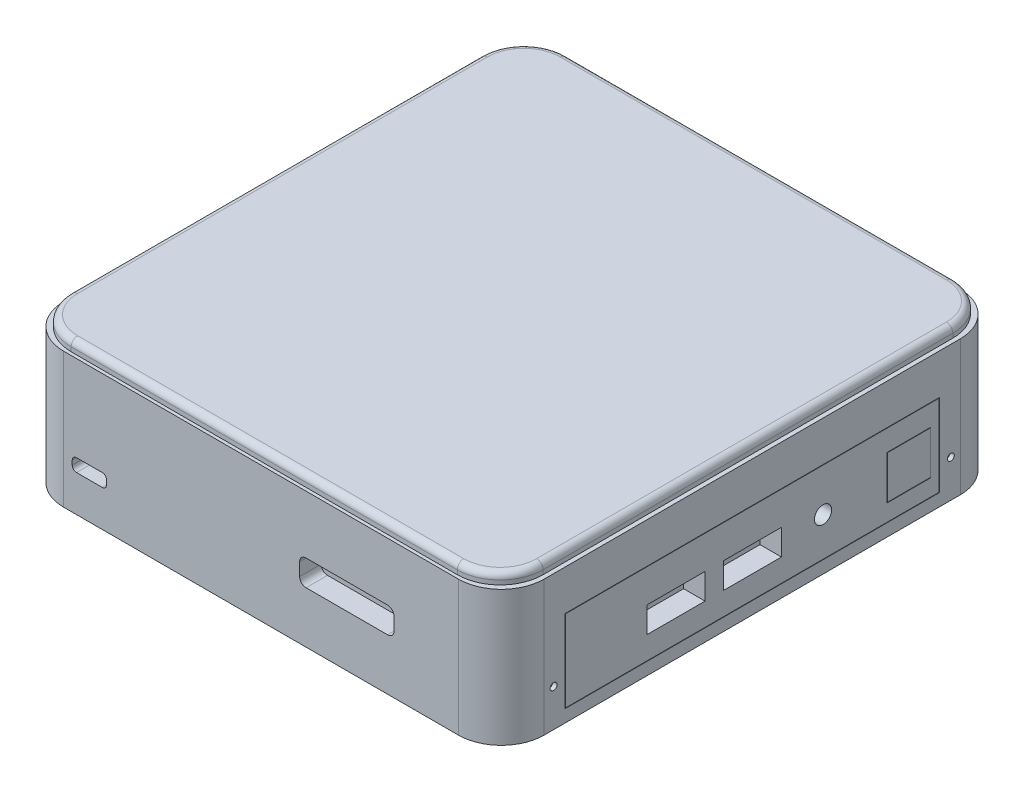
SolidWorks part; units mm, degrees
ref_plane "前视基准面" through (0, 0, 0) normal (0, 0, 1) x (1, 0, 0)
ref_plane "上视基准面" through (0, 0, 0) normal (0, 1, 0) x (1, 0, 0)
ref_plane "右视基准面" through (0, 0, 0) normal (1, 0, 0) x (0, 0, -1)
sketch "草图1" plane through (0, 0, 0) normal (0, 1, 0) x (1, 0, 0)
  line L1 (-56, 58.5) -> (56, 58.5)
  line L2 (-56, 58.5) -> (-56, -58.5)
  line L3 (-56, -58.5) -> (56, -58.5)
  line L4 (56, 58.5) -> (56, -58.5)
  line L5 (0, -58.5) -> (0, 58.5) construction
  line L6 (-56, 0) -> (56, 0) construction
  point P0 (0, 0)
  dimension "D1" = 117
  dimension "D2" = 112
extrude "凸台-拉伸1" add sketch "草图1" along normal blind 34
fillet "圆角1" radius 10 4 edges at (-56, 17, -58.5) (56, 17, -58.5) (56, 17, 58.5) (-56, 17, 58.5)
sketch "草图3" plane through (0, 0, 0) normal (0, 1, 0) x (1, 0, 0)
  line L1 (-44, 56.5) -> (44, 56.5)
  line L2 (-54, 46.5) -> (-54, -46.5)
  line L3 (-44, -56.5) -> (44, -56.5)
  line L4 (54, 46.5) -> (54, -46.5)
  line L5 (0, -56.5) -> (0, 56.5) construction
  line L6 (-54, 0) -> (54, 0) construction
  line L7 (-56, 48.5) -> (-56, -48.5) construction
  line L8 (46, 58.5) -> (-46, 58.5) construction
  arc A0 (-54, -46.5) -> (-44, -56.5) centre (-44, -46.5) ccw
  arc A1 (44, -56.5) -> (54, -46.5) centre (44, -46.5) ccw
  arc A2 (44, 56.5) -> (54, 46.5) centre (44, 46.5) cw
  arc A3 (-44, 56.5) -> (-54, 46.5) centre (-44, 46.5) ccw
  point P7 (0, 0)
  dimension "D3" = 10
  dimension "D1" = 2
  dimension "D2" = 2
extrude "切除-拉伸2" cut sketch "草图3" along normal blind 3 contours L1 A3 L2 A0 L3 A1 L4 A2
sketch "草图2" plane through (0, 0, 0) normal (0, 1, 0) x (1, 0, 0)
  line L0 (0, -58.5) -> (0, 58.5) construction
  line L1 (46, 58.5) -> (-46, 58.5) construction
  line L2 (-56, 0) -> (56, 0) construction
  line L3 (56, -48.5) -> (56, 48.5) construction
  line L4 (56, -48.5) -> (56, 48.5) construction
  line L5 (46, 58.5) -> (-46, 58.5) construction
  circle A0 centre (-45.5, 48) radius 3
  circle A1 centre (-45.5, -48) radius 3
  circle A2 centre (45.5, -48) radius 3
  circle A3 centre (45.5, 48) radius 3
  circle A4 centre (-45.5, 48) radius 5
  circle A5 centre (-45.5, -48) radius 5
  circle A6 centre (45.5, -48) radius 5
  circle A7 centre (45.5, 48) radius 5
  point P8 (0, 0)
  point P12 (0, 0)
  dimension "D1" = 6
  dimension "D2" = 10
  dimension "D3" = 10.5
  dimension "D4" = 10.5
extrude "凸台-拉伸2" add sketch "草图2" against normal blind 2 and the other way up to next
sketch "草图4" plane through (0, 3, 0) normal (0, -1, 0) x (1, 0, 0)
  line L0 (-54, 0) -> (54, 0) construction
  line L1 (-54, -46.5) -> (-54, 46.5) construction
  line L2 (54, -46.5) -> (54, 46.5) construction
  line L3 (0, 0) -> (0, 41.6391) construction
  circle A0 centre (-42.5, 0) radius 1.5
  circle A2 centre (42.5, 0) radius 1.5
  dimension "D1" = 3
  dimension "D2" = 85
extrude "切除-拉伸3" cut sketch "草图4" against normal blind 5
sketch "草图5" plane through (56, 0, 0) normal (1, 0, 0) x (0, 0, -1)
  line L0 (0, 0) -> (0, 34) construction
  line L1 (-48.5, 0) -> (48.5, 0) construction
  line L2 (-48.5, 34) -> (48.5, 34) construction
  line L4 (-43.5, 22) -> (43.5, 22)
  line L5 (-43.5, 22) -> (-43.5, 3)
  line L6 (-43.5, 3) -> (43.5, 3)
  line L7 (43.5, 22) -> (43.5, 3)
  line L8 (0, 3) -> (0, 22) construction
  line L9 (-43.5, 12.5) -> (43.5, 12.5) construction
  line L11 (-43.6, 2.9) -> (43.6, 2.9)
  line L12 (-43.6, 2.9) -> (-43.6, 22.1)
  line L13 (-43.6, 22.1) -> (43.6, 22.1)
  line L14 (43.6, 2.9) -> (43.6, 22.1)
  line L15 (0, 22.1) -> (0, 2.9) construction
  line L16 (-43.6, 12.5) -> (43.6, 12.5) construction
  point P6 (0, 12.5)
  point P11 (0, 12.5)
  dimension "D1" = 87
  dimension "D2" = 19
  dimension "D3" = 3
  dimension "D4" = 0.1
  dimension "D5" = 0.1
sketch "草图6" plane through (56, 0, 0) normal (1, 0, 0) x (0, 0, -1)
  line L0 (0, 0) -> (0, 34) construction
  line L1 (-48.5, 11.3) -> (48.5, 11.3) construction
  line L2 (48.5, 0) -> (48.5, 34) construction
  line L3 (-48.5, 0) -> (48.5, 0) construction
  line L4 (-58.5, 0) -> (-58.5, 34) construction
  line L5 (-24.5, 14.3) -> (-11, 14.3)
  line L6 (-24.5, 14.3) -> (-24.5, 8.3)
  line L7 (-24.5, 8.3) -> (-11, 8.3)
  line L8 (-11, 14.3) -> (-11, 8.3)
  line L9 (-17.75, 8.3) -> (-17.75, 14.3) construction
  line L10 (-24.5, 11.3) -> (-11, 11.3) construction
  line L11 (-6.7, 14.3) -> (6.8, 14.3)
  line L12 (-6.7, 14.3) -> (-6.7, 8.3)
  line L13 (-6.7, 8.3) -> (6.8, 8.3)
  line L14 (6.8, 14.3) -> (6.8, 8.3)
  line L15 (0.05, 8.3) -> (0.05, 14.3) construction
  line L16 (-6.7, 11.3) -> (6.8, 11.3) construction
  line L17 (58.5, 34) -> (58.5, 0) construction
  circle A0 centre (16.5, 12) radius 2
  point P9 (0, 11.3)
  point P11 (-17.75, 11.3)
  point P15 (0.05, 11.3)
  dimension "D2" = 4
  dimension "D3" = 12
  dimension "D1" = 11.3
  dimension "D4" = 6
  dimension "D5" = 6
  dimension "D6" = 13.5
  dimension "D7" = 13.5
  dimension "D8" = 4.3
  dimension "D9" = 34
  dimension "D10" = 42
extrude "切除-拉伸4" cut sketch "草图6" against normal blind 5
extrude "切除-拉伸5" cut sketch "草图5" against normal blind 5
sketch "草图7" plane through (-56, 0, 0) normal (-1, 0, 0) x (0, 0, 1)
  line L0 (-48.5, 0) -> (48.5, 0) construction
  line L1 (-58.5, 0) -> (-58.5, 34) construction
  line L2 (-11, 13) -> (-13.5, 14.4)
  line L7 (-24.5, 14.4) -> (-13.5, 14.4)
  line L8 (-27, 13) -> (-27, 8)
  line L9 (-27, 8) -> (-11, 8)
  line L10 (-11, 13) -> (-11, 8)
  line L11 (-19, 8) -> (-19, 14.4) construction
  line L12 (-27, 10.5) -> (-11, 10.5) construction
  line L13 (-13.5, 14.4) -> (-9.3093, 12.0532)
  line L14 (-27, 13) -> (-24.5, 14.4)
  line L15 (34.8, 17.3) -> (40.8, 17.3) construction
  line L16 (-6, 18.5) -> (8.7, 18.5)
  line L17 (-6, 18.5) -> (-6, 8.5)
  line L18 (-6, 8.5) -> (8.7, 8.5)
  line L19 (8.7, 18.5) -> (8.7, 8.5)
  line L20 (1.35, 8.5) -> (1.35, 18.5) construction
  line L21 (-6, 13.5) -> (8.7, 13.5) construction
  line L22 (4.35, 8.5) -> (-1.65, 8.5)
  line L23 (4.35, 8.5) -> (4.35, 7)
  line L24 (4.35, 7) -> (-1.65, 7)
  line L25 (-1.65, 8.5) -> (-1.65, 7)
  line L26 (1.35, 7) -> (1.35, 8.5) construction
  line L27 (4.35, 7.75) -> (-1.65, 7.75) construction
  line L28 (13.3, 10.7) -> (26.8, 10.7)
  line L29 (13.3, 10.7) -> (13.3, 4.7)
  line L30 (13.3, 4.7) -> (26.8, 4.7)
  line L31 (26.8, 10.7) -> (26.8, 4.7)
  line L32 (20.05, 4.7) -> (20.05, 10.7) construction
  line L33 (13.3, 7.7) -> (26.8, 7.7) construction
  line L34 (13.3, 19.25) -> (26.8, 19.25)
  line L35 (13.3, 19.25) -> (13.3, 13.25)
  line L36 (13.3, 13.25) -> (26.8, 13.25)
  line L37 (26.8, 19.25) -> (26.8, 13.25)
  line L38 (20.05, 13.25) -> (20.05, 19.25) construction
  line L39 (13.3, 16.25) -> (26.8, 16.25) construction
  line L40 (34.8, 19.3) -> (40.8, 19.3)
  line L41 (34.8, 15.3) -> (40.8, 15.3)
  circle A0 centre (-37.25, 14.65) radius 3.25
  arc A1 (34.8, 19.3) -> (34.8, 15.3) centre (34.8, 17.3) ccw
  arc A2 (40.8, 15.3) -> (40.8, 19.3) centre (40.8, 17.3) ccw
  point P6 (-19, 10.5)
  point P8 (1.35, 13.5)
  point P22 (20.05, 7.7)
  point P26 (20.05, 16.25)
  point P32 (37.8, 17.3)
  point P55 (1.35, 7.75)
  dimension "D1" = 6.5
  dimension "D24" = 8
  dimension "D2" = 14.65
  dimension "D3" = 21.25
  dimension "D4" = 8
  dimension "D5" = 16
  dimension "D6" = 10.25
  dimension "D7" = 6.4
  dimension "D8" = 11
  dimension "D9" = 5
  dimension "D10" = 7
  dimension "D11" = 11.5
  dimension "D12" = 10
  dimension "D13" = 14.7
  dimension "D14" = 5
  dimension "D15" = 6
  dimension "D16" = 6
  dimension "D17" = 13.5
  dimension "D18" = 4.6
  dimension "D19" = 2.55
  dimension "D20" = 4.7
  dimension "D21" = 15.3
  dimension "D22" = 4
  dimension "D23" = 6
extrude "切除-拉伸6" cut sketch "草图7" against normal blind 5 contours A0 | L14 L8 L9 L10 L2 L7 | L19 L16 L17 L18 | L18 L25 L24 L23 | L31 L28 L29 L30 | L37 L34 L35 L36 | L41 A2 L40 A1
sketch "草图8" plane through (-56, 0, 0) normal (-1, 0, 0) x (0, 0, 1)
  line L0 (-58.5, 0) -> (-58.5, 34) construction
  line L1 (-34.5, 21) -> (-38.5, 21)
  line L2 (-34.5, 21) -> (-34.5, 29.5)
  line L3 (-34.5, 29.5) -> (-38.5, 29.5)
  line L4 (-38.5, 21) -> (-38.5, 29.5)
  line L5 (-36.5, 29.5) -> (-36.5, 21) construction
  line L6 (-34.5, 25.25) -> (-38.5, 25.25) construction
  line L7 (-48.5, 0) -> (48.5, 0) construction
  line L8 (-29, 21) -> (-29, 29.5)
  line L9 (-29, 21) -> (-33, 21)
  line L10 (-33, 21) -> (-33, 29.5)
  line L11 (-29, 29.5) -> (-33, 29.5)
  line L12 (-23.5, 21) -> (-23.5, 29.5)
  line L13 (-23.5, 21) -> (-27.5, 21)
  line L14 (-27.5, 21) -> (-27.5, 29.5)
  line L15 (-23.5, 29.5) -> (-27.5, 29.5)
  line L16 (-18, 21) -> (-18, 29.5)
  line L17 (-18, 21) -> (-22, 21)
  line L18 (-22, 21) -> (-22, 29.5)
  line L19 (-18, 29.5) -> (-22, 29.5)
  line L20 (-12.5, 21) -> (-12.5, 29.5)
  line L21 (-12.5, 21) -> (-16.5, 21)
  line L22 (-16.5, 21) -> (-16.5, 29.5)
  line L23 (-12.5, 29.5) -> (-16.5, 29.5)
  line L24 (-7, 21) -> (-7, 29.5)
  line L25 (-7, 21) -> (-11, 21)
  line L26 (-11, 21) -> (-11, 29.5)
  line L27 (-7, 29.5) -> (-11, 29.5)
  line L28 (-1.5, 21) -> (-1.5, 29.5)
  line L29 (-1.5, 21) -> (-5.5, 21)
  line L30 (-5.5, 21) -> (-5.5, 29.5)
  line L31 (-1.5, 29.5) -> (-5.5, 29.5)
  line L32 (4, 21) -> (4, 29.5)
  line L33 (4, 21) -> (0, 21)
  line L34 (0, 21) -> (0, 29.5)
  line L35 (4, 29.5) -> (0, 29.5)
  line L36 (9.5, 21) -> (9.5, 29.5)
  line L37 (9.5, 21) -> (5.5, 21)
  line L38 (5.5, 21) -> (5.5, 29.5)
  line L39 (9.5, 29.5) -> (5.5, 29.5)
  line L40 (15, 21) -> (15, 29.5)
  line L41 (15, 21) -> (11, 21)
  line L42 (11, 21) -> (11, 29.5)
  line L43 (15, 29.5) -> (11, 29.5)
  line L44 (20.5, 21) -> (20.5, 29.5)
  line L45 (20.5, 21) -> (16.5, 21)
  line L46 (16.5, 21) -> (16.5, 29.5)
  line L47 (20.5, 29.5) -> (16.5, 29.5)
  line L48 (26, 21) -> (26, 29.5)
  line L49 (26, 21) -> (22, 21)
  line L50 (22, 21) -> (22, 29.5)
  line L51 (26, 29.5) -> (22, 29.5)
  line L52 (31.5, 21) -> (31.5, 29.5)
  line L53 (31.5, 21) -> (27.5, 21)
  line L54 (27.5, 21) -> (27.5, 29.5)
  line L55 (31.5, 29.5) -> (27.5, 29.5)
  line L56 (37, 21) -> (37, 29.5)
  line L57 (37, 21) -> (33, 21)
  line L58 (33, 21) -> (33, 29.5)
  line L59 (37, 29.5) -> (33, 29.5)
  point P0 (-36.5, 25.25)
  dimension "D1" = 20
  dimension "D2" = 8.5
  dimension "D3" = 21
  dimension "D4" = 4
  dimension "D5" = 14
extrude "切除-拉伸7" cut sketch "草图8" against normal blind 5
sketch "草图9" plane through (0, 0, 58.5) normal (0, 0, 1) x (1, 0, 0)
  line L0 (-46, 0) -> (46, 0) construction
  line L1 (-44, 11.5) -> (-36, 11.5)
  line L2 (-44, 11.5) -> (-44, 8.5)
  line L3 (-44, 8.5) -> (-36, 8.5)
  line L4 (-36, 11.5) -> (-36, 8.5)
  line L5 (-40, 8.5) -> (-40, 11.5) construction
  line L6 (-44, 10) -> (-36, 10) construction
  line L7 (-56, 0) -> (-56, 34) construction
  point P0 (-40, 10)
  dimension "D1" = 8.5
  dimension "D2" = 3
  dimension "D3" = 8
  dimension "D4" = 12
extrude "切除-拉伸8" cut sketch "草图9" against normal blind 5
sketch "草图10" plane through (0, 0, 58.5) normal (0, 0, 1) x (1, 0, 0)
  line L0 (-46, 0) -> (46, 0) construction
  line L1 (9, 18) -> (31, 18)
  line L2 (9, 18) -> (9, 12)
  line L3 (9, 12) -> (31, 12)
  line L4 (31, 18) -> (31, 12)
  line L5 (20, 12) -> (20, 18) construction
  line L6 (9, 15) -> (31, 15) construction
  line L7 (56, 34) -> (56, 0) construction
  point P0 (20, 15)
  dimension "D1" = 12
  dimension "D2" = 22
  dimension "D3" = 6
  dimension "D4" = 25
extrude "切除-拉伸9" cut sketch "草图10" against normal blind 5
sketch "草图12" plane through (0, 0, 53.5) normal (0, 0, 1) x (1, 0, 0)
  line L0 (9, 15) -> (31, 15) construction
  line L1 (9, 18) -> (9, 12) construction
  line L2 (31, 12) -> (31, 18) construction
  line L3 (31, 12) -> (31, 18) construction
  line L4 (16, 16) -> (28, 16)
  line L5 (16, 16) -> (16, 14)
  line L6 (16, 14) -> (28, 14)
  line L7 (28, 16) -> (28, 14)
  line L8 (22, 14) -> (22, 16) construction
  line L9 (16, 15) -> (28, 15) construction
  point P6 (22, 15)
  dimension "D1" = 12
  dimension "D2" = 3
  dimension "D3" = 2
extrude "切除-拉伸10" cut sketch "草图12" against normal blind 5
fillet "圆角2" radius 1.5 4 edges at (31, 12, 56) (9, 12, 56) (31, 18, 56) (9, 18, 56)
fillet "圆角3" radius 0.5 4 edges at (16, 16, 51) (28, 14, 51) (28, 16, 51) (16, 14, 51)
fillet "圆角4" radius 1 4 edges at (-44, 8.5, 56) (-36, 8.5, 56) (-44, 11.5, 56) (-36, 11.5, 56)
fillet "圆角6" radius 1 57 edges at (-53.5, 18.5, -6) (-53.5, 21, 33) (-53.5, 21, 37) (-53.5, 29.5, 37) (-53.5, 29.5, 33) (-53.5, 21, 27.5) (-53.5, 21, 31.5) (-53.5, 29.5, 31.5) (-53.5, 29.5, 27.5) (-53.5, 21, 22) (-53.5, 21, 26) (-53.5, 29.5, 26) (-53.5, 29.5, 22) (-53.5, 21, 16.5) (-53.5, 21, 20.5) (-53.5, 29.5, 20.5) (-53.5, 29.5, 16.5) (-53.5, 21, 11) (-53.5, 21, 15) (-53.5, 29.5, 15) (-53.5, 29.5, 11) (-53.5, 21, 5.5) (-53.5, 21, 9.5) (-53.5, 29.5, 9.5) (-53.5, 29.5, 5.5) (-53.5, 21, 0) (-53.5, 21, 4) (-53.5, 29.5, 4) (-53.5, 29.5, 0) (-53.5, 21, -5.5) (-53.5, 21, -1.5) (-53.5, 29.5, -1.5) (-53.5, 29.5, -5.5) (-53.5, 21, -11) (-53.5, 21, -7) (-53.5, 29.5, -7) (-53.5, 29.5, -11) (-53.5, 21, -16.5) (-53.5, 21, -12.5) (-53.5, 29.5, -12.5) (-53.5, 29.5, -16.5) (-53.5, 21, -22) (-53.5, 21, -18) (-53.5, 29.5, -18) (-53.5, 29.5, -22) (-53.5, 21, -27.5) (-53.5, 21, -23.5) (-53.5, 29.5, -23.5) (-53.5, 29.5, -27.5) (-53.5, 21, -33) (-53.5, 21, -29) (-53.5, 29.5, -29) (-53.5, 29.5, -33) (-53.5, 21, -34.5) (-53.5, 29.5, -34.5) (-53.5, 21, -38.5) (-53.5, 29.5, -38.5)
sketch "草图13" plane through (56, 0, 0) normal (1, 0, 0) x (0, 0, -1)
  line L0 (-48.5, 0) -> (48.5, 0) construction
  line L1 (31.5, 17) -> (41.5, 17)
  line L2 (31.5, 17) -> (31.5, 7)
  line L3 (31.5, 7) -> (41.5, 7)
  line L4 (41.5, 17) -> (41.5, 7)
  line L5 (36.5, 7) -> (36.5, 17) construction
  line L6 (31.5, 12) -> (41.5, 12) construction
  line L7 (58.5, 34) -> (58.5, 0) construction
  line L9 (31.4, 17.1) -> (41.6, 17.1)
  line L10 (31.4, 17.1) -> (31.4, 6.9)
  line L11 (31.4, 6.9) -> (41.6, 6.9)
  line L12 (41.6, 17.1) -> (41.6, 6.9)
  line L13 (36.5, 6.9) -> (36.5, 17.1) construction
  line L14 (31.4, 12) -> (41.6, 12) construction
  point P0 (36.5, 12)
  point P8 (36.5, 12)
  dimension "D1" = 7
  dimension "D2" = 10
  dimension "D3" = 10
  dimension "D4" = 17
  dimension "D5" = 0.1
  dimension "D6" = 0.1
extrude "切除-拉伸11" cut sketch "草图13" against normal blind 5
sketch "草图14" plane through (0, 34, 0) normal (0, 1, 0) x (1, 0, 0)
  line L1 (-45, 57.75) -> (45, 57.75)
  line L2 (-55, 47.75) -> (-55, -47.75)
  line L3 (-45, -57.75) -> (45, -57.75)
  line L4 (55, 47.75) -> (55, -47.75)
  line L5 (0, -57.75) -> (0, 57.75) construction
  line L6 (-55, 0) -> (55, 0) construction
  line L8 (56, -48.5) -> (56, 48.5) construction
  line L9 (-46, 58.5) -> (46, 58.5)
  line L10 (-56, 48.5) -> (-56, -48.5)
  line L11 (-46, -58.5) -> (46, -58.5)
  line L12 (56, 48.5) -> (56, -48.5)
  line L13 (0, -58.5) -> (0, 58.5) construction
  line L14 (-56, 0) -> (56, 0) construction
  line L15 (-46, -58.5) -> (46, -58.5) construction
  arc A0 (-55, -47.75) -> (-45, -57.75) centre (-45, -47.75) ccw
  arc A1 (-56, -48.5) -> (-46, -58.5) centre (-46, -48.5) ccw
  arc A2 (45, -57.75) -> (55, -47.75) centre (45, -47.75) ccw
  arc A3 (46, -58.5) -> (56, -48.5) centre (46, -48.5) ccw
  arc A4 (46, 58.5) -> (56, 48.5) centre (46, 48.5) cw
  arc A5 (45, 57.75) -> (55, 47.75) centre (45, 47.75) cw
  arc A6 (-45, 57.75) -> (-55, 47.75) centre (-45, 47.75) ccw
  arc A7 (-46, 58.5) -> (-56, 48.5) centre (-46, 48.5) ccw
  point P0 (0, 0)
  point P4 (0, 0)
  point P14 (-55, -57.75)
  point P19 (55, -57.75)
  point P27 (55, 57.75)
  dimension "D3" = 10
  dimension "D1" = 110
  dimension "D2" = 115.5
extrude "切除-拉伸12" cut sketch "草图14" against normal blind 2.5
fillet "圆角7" radius 1.5 8 edges at (52.0711, 34, 54.8211) (55, 34, 0) (52.0711, 34, -54.8211) (0, 34, -57.75) (-52.0711, 34, -54.8211) (-55, 34, 0) (-52.0711, 34, 54.8211) (0, 34, 57.75)
sketch "草图15" plane through (0, 3, 0) normal (0, -1, 0) x (1, 0, 0)
  line L0 (0, 0) -> (0, 56.5) construction
  line L1 (-44, 56.5) -> (44, 56.5) construction
  line L2 (0, 0) -> (-54, 0) construction
  line L3 (-54, -46.5) -> (-54, 46.5) construction
  circle A0 centre (-45.5, 48) radius 3
  circle A1 centre (-45.5, -48) radius 3
  circle A2 centre (45.5, 48) radius 3
  circle A3 centre (45.5, -48) radius 3
  dimension "D1" = 6
extrude "凸台-拉伸3" add sketch "草图15" along normal blind 3.5
sketch "草图16" plane through (0, -0.5, 0) normal (0, -1, 0) x (1, 0, 0)
  line L0 (-43.3787, 45.8787) -> (-47.6213, 50.1213) construction
  line L1 (-47.6213, 45.8787) -> (-43.3787, 50.1213) construction
  line L6 (-45.7828, 48) -> (-48.5, 48) construction
  line L7 (-45.7828, 48) -> (-46.8789, 49.096)
  line L8 (-46.8789, 49.096) -> (-46.596, 49.3789)
  line L9 (-46.596, 49.3789) -> (-45.5, 48.2828)
  line L11 (-45.2172, 48) -> (-44.1211, 46.904)
  line L12 (-44.1211, 46.904) -> (-44.404, 46.6211)
  line L13 (-44.404, 46.6211) -> (-45.5, 47.7172)
  line L15 (-45.5, 48.2828) -> (-44.404, 49.3789)
  line L16 (-44.404, 49.3789) -> (-44.1211, 49.096)
  line L17 (-44.1211, 49.096) -> (-45.2172, 48)
  line L18 (-45.5, 47.7172) -> (-46.596, 46.6211)
  line L19 (-46.596, 46.6211) -> (-46.8789, 46.904)
  line L20 (-46.8789, 46.904) -> (-45.7828, 48)
  line L21 (-46.8789, 46.904) -> (-45.7828, 48)
  line L22 (0, 0) -> (0, 56.2429) construction
  line L23 (0, 0) -> (-53.9938, 0) construction
  line L24 (-45.7828, -48) -> (-48.5, -48) construction
  line L25 (-47.6213, -45.8787) -> (-43.3787, -50.1213) construction
  line L26 (-43.3787, -45.8787) -> (-47.6213, -50.1213) construction
  line L27 (-46.8789, -46.904) -> (-45.7828, -48)
  line L28 (-46.8789, -46.904) -> (-45.7828, -48)
  line L29 (-46.596, -46.6211) -> (-46.8789, -46.904)
  line L30 (-45.5, -47.7172) -> (-46.596, -46.6211)
  line L31 (-44.1211, -49.096) -> (-45.2172, -48)
  line L32 (-44.404, -49.3789) -> (-44.1211, -49.096)
  line L33 (-45.5, -48.2828) -> (-44.404, -49.3789)
  line L34 (-44.404, -46.6211) -> (-45.5, -47.7172)
  line L35 (-44.1211, -46.904) -> (-44.404, -46.6211)
  line L36 (-45.2172, -48) -> (-44.1211, -46.904)
  line L37 (-46.596, -49.3789) -> (-45.5, -48.2828)
  line L38 (-46.8789, -49.096) -> (-46.596, -49.3789)
  line L39 (-45.7828, -48) -> (-46.8789, -49.096)
  line L40 (43.3787, -45.8787) -> (47.6213, -50.1213) construction
  line L41 (47.6213, -45.8787) -> (43.3787, -50.1213) construction
  line L42 (45.7828, -48) -> (48.5, -48) construction
  line L43 (45.7828, -48) -> (46.8789, -49.096)
  line L44 (46.8789, -49.096) -> (46.596, -49.3789)
  line L45 (46.596, -49.3789) -> (45.5, -48.2828)
  line L46 (45.2172, -48) -> (44.1211, -46.904)
  line L47 (44.1211, -46.904) -> (44.404, -46.6211)
  line L48 (44.404, -46.6211) -> (45.5, -47.7172)
  line L49 (45.5, -48.2828) -> (44.404, -49.3789)
  line L50 (44.404, -49.3789) -> (44.1211, -49.096)
  line L51 (44.1211, -49.096) -> (45.2172, -48)
  line L52 (45.5, -47.7172) -> (46.596, -46.6211)
  line L53 (46.596, -46.6211) -> (46.8789, -46.904)
  line L54 (46.8789, -46.904) -> (45.7828, -48)
  line L55 (46.8789, -46.904) -> (45.7828, -48)
  line L56 (45.7828, 48) -> (48.5, 48) construction
  line L57 (47.6213, 45.8787) -> (43.3787, 50.1213) construction
  line L58 (43.3787, 45.8787) -> (47.6213, 50.1213) construction
  line L59 (46.8789, 46.904) -> (45.7828, 48)
  line L60 (46.8789, 46.904) -> (45.7828, 48)
  line L61 (46.596, 46.6211) -> (46.8789, 46.904)
  line L62 (45.5, 47.7172) -> (46.596, 46.6211)
  line L63 (44.1211, 49.096) -> (45.2172, 48)
  line L64 (44.404, 49.3789) -> (44.1211, 49.096)
  line L65 (45.5, 48.2828) -> (44.404, 49.3789)
  line L66 (44.404, 46.6211) -> (45.5, 47.7172)
  line L67 (44.1211, 46.904) -> (44.404, 46.6211)
  line L68 (45.2172, 48) -> (44.1211, 46.904)
  line L69 (46.596, 49.3789) -> (45.5, 48.2828)
  line L70 (46.8789, 49.096) -> (46.596, 49.3789)
  line L71 (45.7828, 48) -> (46.8789, 49.096)
  circle A1 centre (-45.5, 48) radius 3 construction
  circle A2 centre (-45.5, 48) radius 3 construction
  point P7 (-45.5, 48)
  point P12 (-45.5, 48)
  point P43 (-45.5, -48)
  point P61 (45.5, -48)
  point P79 (45.5, 48)
  dimension "D1" = 45
  dimension "D2" = 2.7172
  dimension "D3" = 3
  dimension "D4" = 1.55
  dimension "D5" = 0.4
  dimension "D6" = 0.4
  dimension "D7" = 45
extrude "切除-拉伸13" cut sketch "草图16" against normal blind 1 contours L20 L19 L18 L13 L12 L11 L17 L16 L15 L9 L8 L7 | L27 L39 L38 L37 L33 L32 L31 L36 L35 L34 L30 L29 | L54 L53 L52 L48 L47 L46 L51 L50 L49 L45 L44 L43 | L59 L71 L70 L69 L65 L64 L63 L68 L67 L66 L62 L61
sketch "草图17" plane through (56, 0, 0) normal (1, 0, 0) x (0, 0, -1)
  line L0 (-48.5, 8.7) -> (48.5, 8.7) construction
  line L1 (-48.5, 31.5) -> (-48.5, 0) construction
  line L2 (48.5, 0) -> (48.5, 31.5) construction
  line L3 (-48.5, 0) -> (48.5, 0) construction
  line L4 (0, 8.7) -> (0, 0) construction
  circle A0 centre (-46.3, 8.7) radius 0.8
  circle A1 centre (46.3, 8.7) radius 0.8
  dimension "D2" = 1.6
  dimension "D1" = 8.7
  dimension "D3" = 92.6
extrude "切除-拉伸14" cut sketch "草图17" against normal blind 1
sketch "草图18" plane through (0, 0, -58.5) normal (0, 0, -1) x (-1, 0, 0)
  line L0 (-46, 0) -> (46, 0) construction
  line L1 (-32.5, 25) -> (32.5, 25)
  line L2 (-32.5, 25) -> (-32.5, 5)
  line L3 (-32.5, 5) -> (32.5, 5)
  line L4 (32.5, 25) -> (32.5, 5)
  line L5 (0, 5) -> (0, 25) construction
  line L6 (-32.5, 15) -> (32.5, 15) construction
  line L7 (-56, 0) -> (-56, 31.5) construction
  line L9 (-32.4, 24.9) -> (32.4, 24.9)
  line L10 (-32.4, 24.9) -> (-32.4, 5.1)
  line L11 (-32.4, 5.1) -> (32.4, 5.1)
  line L12 (32.4, 24.9) -> (32.4, 5.1)
  line L13 (0, 5.1) -> (0, 24.9) construction
  line L14 (-32.4, 15) -> (32.4, 15) construction
  point P0 (0, 15)
  point P8 (0, 15)
  dimension "D1" = 65
  dimension "D2" = 20
  dimension "D3" = 5
  dimension "D4" = 23.5
  dimension "D5" = 0.1
  dimension "D6" = 0.1
extrude "切除-拉伸15" cut sketch "草图18" against normal blind 10 contours L4 L1 L2 L3 L9 L12 L11 L10
